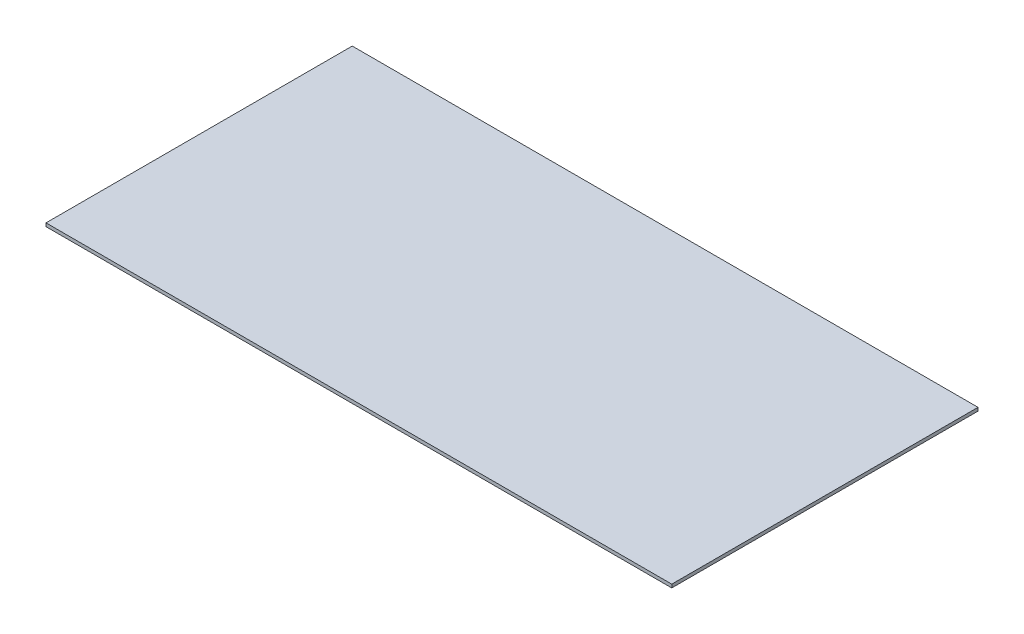
SolidWorks part; units mm, degrees
material "Glass"
ref_plane "Front Plane" through (0, 0, 0) normal (0, 0, 1) x (1, 0, 0)
ref_plane "Top Plane" through (0, 0, 0) normal (0, 1, 0) x (1, 0, 0)
ref_plane "Right Plane" through (0, 0, 0) normal (1, 0, 0) x (0, 0, -1)
sketch "Sketch1" plane through (0, 0, 0) normal (0, 1, 0) x (1, 0, 0)
  line L1 (0, 0) -> (566, 0)
  line L2 (0, 0) -> (0, 277)
  line L3 (0, 277) -> (566, 277)
  line L4 (566, 0) -> (566, 277)
  dimension "D1" = 277
  dimension "D2" = 566
extrude "Boss-Extrude1" add sketch "Sketch1" along normal blind 3
